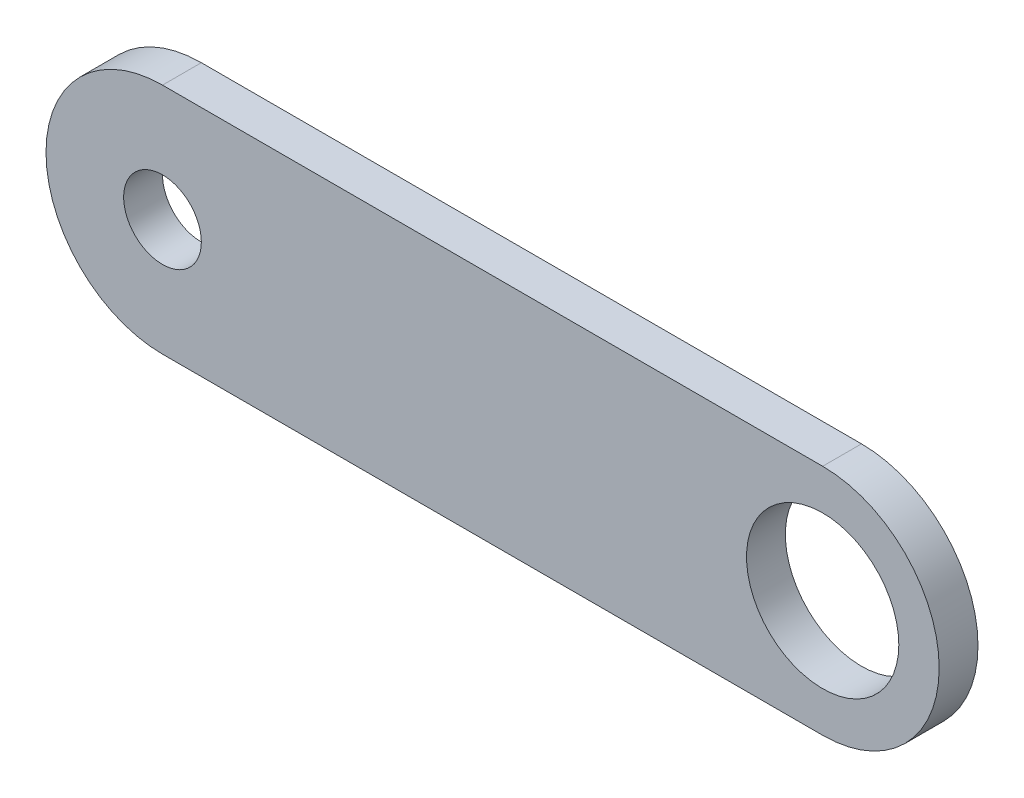
SolidWorks part; units mm, degrees
material "Fundición gris (SN)"
ref_plane "Alzado" through (0, 0, 0) normal (0, 0, 1) x (1, 0, 0)
ref_plane "Planta" through (0, 0, 0) normal (0, 1, 0) x (1, 0, 0)
ref_plane "Vista lateral" through (0, 0, 0) normal (1, 0, 0) x (0, 0, -1)
sketch "Croquis1" plane through (0, 0, 0) normal (0, 0, 1) x (1, 0, 0)
  line L0 (-8.5, 0) -> (8.5, 0) construction
  line L1 (-8.5, 3) -> (8.5, 3)
  line L2 (-8.5, -3) -> (8.5, -3)
  arc A0 (-8.5, 3) -> (-8.5, -3) centre (-8.5, 0) ccw
  arc A1 (8.5, -3) -> (8.5, 3) centre (8.5, 0) ccw
  circle A2 centre (8.5, 0) radius 1.9607
  circle A3 centre (-8.5, 0) radius 1
  point P2 (0, 0)
  dimension "D2" = 3
  dimension "D3" = 2
  dimension "D1" = 17
extrude "Saliente-Extruir1" add sketch "Croquis1" along normal blind 1
